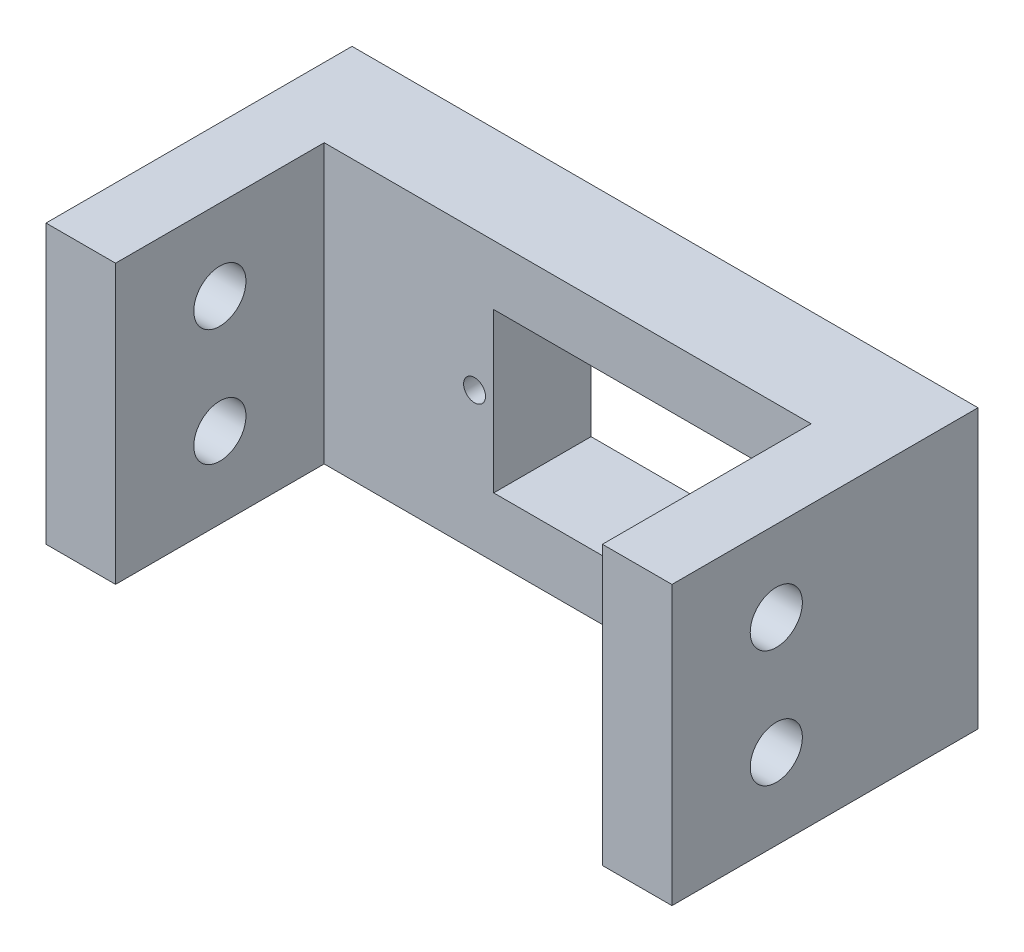
SolidWorks part; units mm, degrees
ref_plane "Front Plane" through (0, 0, 0) normal (0, 0, 1) x (1, 0, 0)
ref_plane "Top Plane" through (0, 0, 0) normal (0, 1, 0) x (1, 0, 0)
ref_plane "Right Plane" through (0, 0, 0) normal (1, 0, 0) x (0, 0, -1)
sketch "Sketch1" plane through (0, 0, 0) normal (0, 1, 0) x (1, 0, 0)
  line L0 (-28.575, 8.89) -> (28.575, 8.89)
  line L1 (28.575, 8.89) -> (28.575, -19.05)
  line L2 (28.575, -19.05) -> (22.225, -19.05)
  line L3 (22.225, -19.05) -> (22.225, 0)
  line L4 (22.225, 0) -> (-22.225, 0)
  line L5 (0, 0) -> (0, 8.89) construction
  line L6 (-22.225, -19.05) -> (-22.225, 0)
  line L7 (-28.575, -19.05) -> (-22.225, -19.05)
  line L8 (-28.575, 8.89) -> (-28.575, -19.05)
  point P10 (0, 0)
  point P12 (0, 0)
  point P13 (0, 0)
  dimension "D1" = 44.45
  dimension "D2" = 6.35
  dimension "D3" = 8.89
  dimension "D4" = 19.05
extrude "Boss-Extrude1" add sketch "Sketch1" along normal blind 25.4
sketch "Sketch2" plane through (22.225, 0, 0) normal (-1, 0, 0) x (0, 0, 1)
  line L0 (0, 12.7) -> (19.05, 12.7) construction
  line L1 (0, 25.4) -> (0, 0) construction
  line L2 (19.05, 25.4) -> (19.05, 0) construction
  line L3 (9.525, 25.4) -> (9.525, 0) construction
  line L4 (0, 25.4) -> (19.05, 25.4) construction
  line L5 (0, 0) -> (19.05, 0) construction
  circle A0 centre (9.525, 18.034) radius 2.3813
  circle A1 centre (9.525, 7.366) radius 2.3813
  point P16 (0, 0)
  point P17 (9.525, 18.4038)
  dimension "D1" = 4.7625
  dimension "D2" = 10.668
extrude "Cut-Extrude1" cut sketch "Sketch2" against normal through all both and the other way through all
sketch "Sketch3" plane through (0, 0, -8.89) normal (0, 0, -1) x (-1, 0, 0)
  line L0 (0, 25.4) -> (0, 0) construction
  line L1 (-28.575, 25.4) -> (28.575, 25.4) construction
  line L2 (-28.575, 12.7) -> (28.575, 12.7) construction
  line L3 (-28.575, 25.4) -> (-28.575, 0) construction
  line L4 (28.575, 25.4) -> (28.575, 0) construction
  line L5 (-19, 12.7) -> (-17.25, 12.7) construction
  line L6 (-17.25, 19.95) -> (6.75, 19.95)
  line L7 (-17.25, 19.95) -> (-17.25, 5.45)
  line L8 (-17.25, 5.45) -> (6.75, 5.45)
  line L9 (6.75, 19.95) -> (6.75, 5.45)
  line L10 (8.5, 12.7) -> (6.75, 12.7) construction
  circle A0 centre (8.5, 12.7) radius 1
  circle A1 centre (-19, 12.7) radius 1
  point P15 (-17.25, 12.7)
  point P16 (0, 12.7)
  point P17 (0, 12.7)
  dimension "D1" = 2
  dimension "D2" = 27.5
  dimension "D3" = 8.5
  dimension "D4" = 24
  dimension "D5" = 14.5
extrude "Cut-Extrude2" cut sketch "Sketch3" against normal through all
